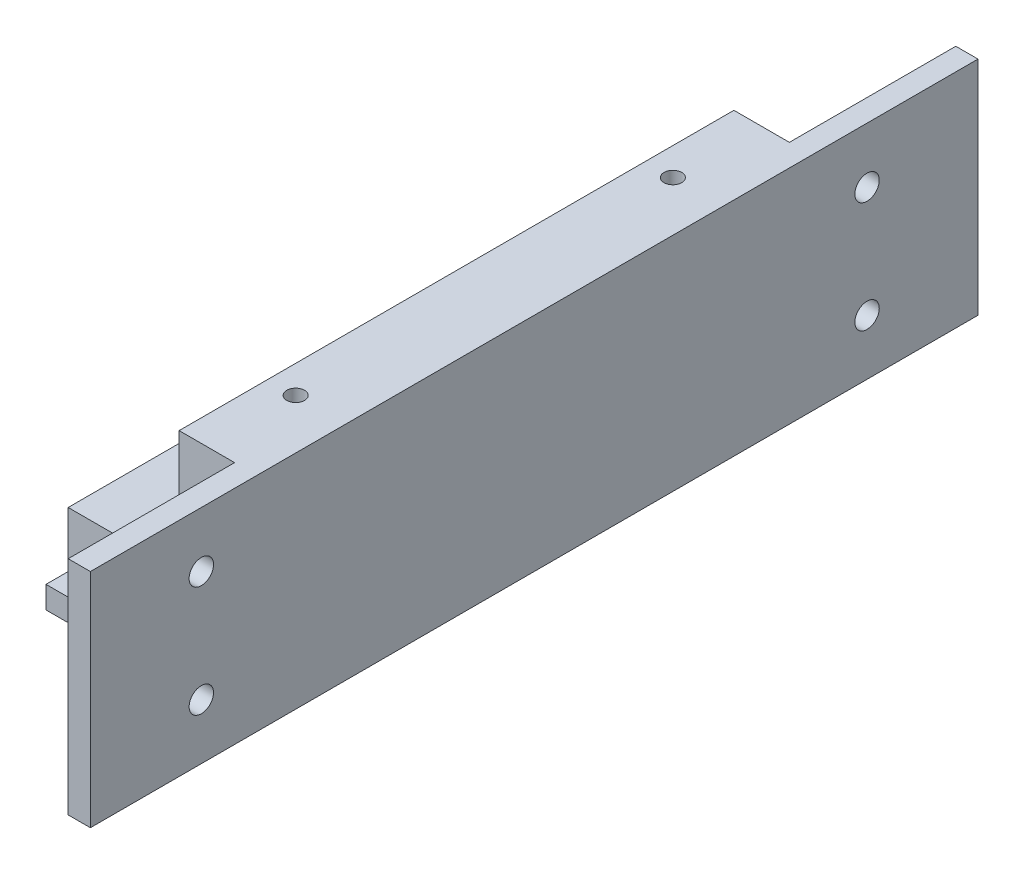
SolidWorks part; units mm, degrees
ref_plane "前视基准面" through (0, 0, 0) normal (0, 0, 1) x (1, 0, 0)
ref_plane "上视基准面" through (0, 0, 0) normal (0, 1, 0) x (1, 0, 0)
ref_plane "右视基准面" through (0, 0, 0) normal (1, 0, 0) x (0, 0, -1)
other "Configuration Table"
sketch "草图1" plane through (0, 0, 0) normal (0, 1, 0) x (1, 0, 0)
  line L5 (-1, -25) -> (1, -25)
  line L6 (-1, -25) -> (-1, 25)
  line L7 (-1, 25) -> (1, 25)
  line L8 (1, -25) -> (1, 25)
  line L9 (-1, -25) -> (1, 25) construction
  line L10 (-1, 25) -> (1, -25) construction
  point P0 (0, 0)
  dimension "D1" = 2
  dimension "D2" = 50
extrude "凸台-拉伸1" add sketch "草图1" along normal blind 2
sketch "草图3" plane through (1, 0, 0) normal (1, 0, 0) x (0, 0, -1)
  line L1 (-25, 0) -> (25, 0)
  line L2 (-25, 0) -> (-25, 20)
  line L3 (-25, 20) -> (25, 20)
  line L4 (25, 0) -> (25, 20)
  point P5 (25, 0)
  dimension "D1" = 20
extrude "凸台-拉伸3" add sketch "草图3" along normal blind 20
sketch "草图4" plane through (0, 0, 25) normal (0, 0, 1) x (1, 0, 0)
  line L1 (1, 20) -> (11, 20)
  line L2 (1, 20) -> (1, 9)
  line L3 (1, 9) -> (11, 9)
  line L4 (11, 20) -> (11, 9)
  dimension "D1" = 11
  dimension "D2" = 10
extrude "切除-拉伸1" cut sketch "草图4" against normal through all
sketch "草图6" plane through (21, 0, 0) normal (1, 0, 0) x (0, 0, -1)
  line L1 (-40, 20) -> (-25, 20)
  line L2 (-40, 20) -> (-40, 0)
  line L3 (-40, 0) -> (-25, 0)
  line L4 (-25, 20) -> (-25, 0)
  line L5 (25, 0) -> (40, 0)
  line L6 (25, 0) -> (25, 20)
  line L7 (25, 20) -> (40, 20)
  line L8 (40, 0) -> (40, 20)
  point P12 (50.4204, 0)
  dimension "D1" = 15
  dimension "D2" = 20
  dimension "D3" = 15
extrude "凸台-拉伸4" add sketch "草图6" against normal blind 5
sketch "草图7" plane through (0, 20, 0) normal (0, 1, 0) x (1, 0, 0)
  line L1 (21, -40) -> (18, -40)
  line L2 (21, -40) -> (21, 40)
  line L3 (21, 40) -> (18, 40)
  line L4 (18, -40) -> (18, 40)
  dimension "D1" = 3
extrude "切除-拉伸4" cut sketch "草图7" against normal through all
sketch "草图8" plane through (18, 0, 0) normal (1, 0, 0) x (0, 0, -1)
  line L0 (40, 0) -> (40, 20) construction
  line L1 (40, 20) -> (-40, 20) construction
  line L2 (40, 0) -> (-40, 0) construction
  line L3 (30, 15) -> (30, 5)
  line L4 (-40, 0) -> (-40, 20) construction
  line L5 (-30, 15) -> (-30, 5)
  circle A0 centre (30, 15) radius 1.1
  circle A1 centre (30, 5) radius 1.1
  circle A2 centre (-30, 15) radius 1.1
  circle A3 centre (-30, 5) radius 1.1
  point P16 (0, 0)
  point P17 (0, 0)
  dimension "D4" = 2.2
  dimension "D1" = 10
  dimension "D2" = 5
  dimension "D3" = 5
  dimension "D5" = 10
extrude "切除-拉伸5" cut sketch "草图8" against normal through all contours A0 | A1 | A2 | A3
sketch "草图9" plane through (0, 20, 0) normal (0, 1, 0) x (1, 0, 0)
  line L1 (11, 25) -> (11, -25) construction
  line L2 (13.5, -17) -> (13.5, 17)
  line L3 (16, -25) -> (11, -25) construction
  line L4 (16, 25) -> (11, 25) construction
  circle A0 centre (13.5, -17) radius 0.8
  circle A1 centre (13.5, 17) radius 0.8
  dimension "D2" = 1.6
  dimension "D1" = 2.5
  dimension "D3" = 8
  dimension "D4" = 8
extrude "切除-拉伸6" cut sketch "草图9" against normal blind 2 contours A1 | A0
